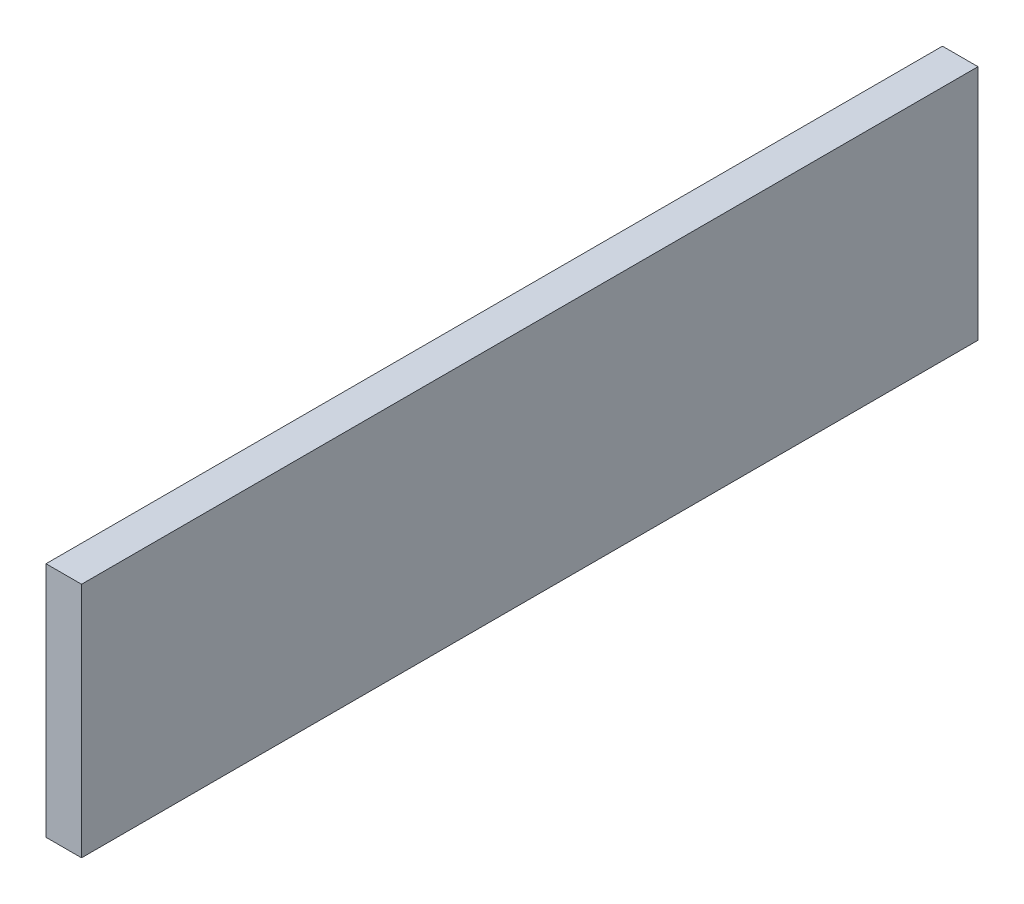
SolidWorks part; units mm, degrees
ref_plane "Front Plane" through (0, 0, 0) normal (0, 0, 1) x (1, 0, 0)
ref_plane "Top Plane" through (0, 0, 0) normal (0, 1, 0) x (1, 0, 0)
ref_plane "Right Plane" through (0, 0, 0) normal (1, 0, 0) x (0, 0, -1)
sketch "Sketch1" plane through (0, 0, 0) normal (1, 0, 0) x (0, 0, -1)
  line L1 (0, 0) -> (454, 0)
  line L2 (0, 0) -> (0, 120)
  line L3 (0, 120) -> (454, 120)
  line L4 (454, 0) -> (454, 120)
  dimension "D1" = 454
  dimension "D2" = 120
extrude "Boss-Extrude1" add sketch "Sketch1" along normal blind 18
